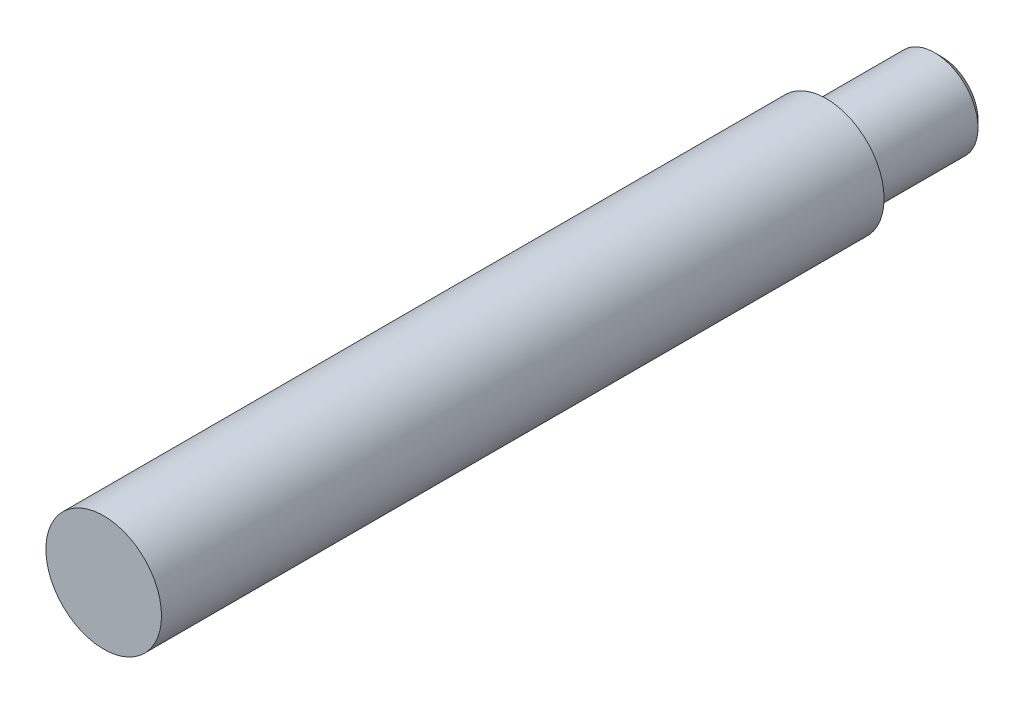
SolidWorks part; units mm, degrees
ref_plane "Front" through (0, 0, 0) normal (0, 0, 1) x (1, 0, 0)
ref_plane "Top" through (0, 0, 0) normal (0, 1, 0) x (1, 0, 0)
ref_plane "Right" through (0, 0, 0) normal (1, 0, 0) x (0, 0, -1)
sketch "Esquisse1" plane through (0, 0, 0) normal (0, 0, 1) x (1, 0, 0)
  circle A0 centre (0, 0) radius 3
  dimension "D1" = 6
extrude "Boss.-Extru.1" add sketch "Esquisse1" along normal blind 8
chamfer "Chanfrein1" distance 0.5 angle 45 1 edges at (3, 0, 0)
sketch "Esquisse2" plane through (0, 0, 8) normal (0, 0, 1) x (1, 0, 0)
  circle A0 centre (0, 0) radius 4
  dimension "D1" = 8
extrude "Boss.-Extru.2" add sketch "Esquisse2" along normal blind 50
